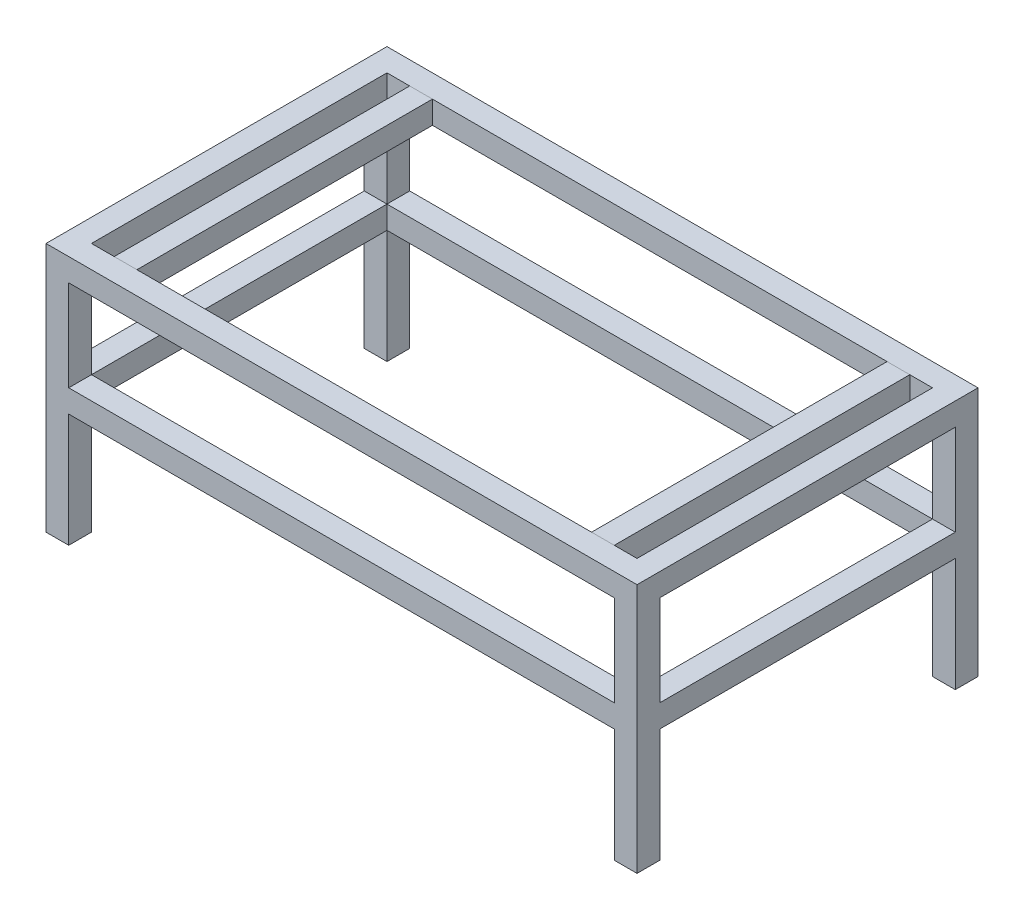
SolidWorks part; units mm, degrees
ref_plane "Plan de face" through (0, 0, 0) normal (0, 0, 1) x (1, 0, 0)
ref_plane "Plan de dessus" through (0, 0, 0) normal (0, 1, 0) x (1, 0, 0)
ref_plane "Plan de droite" through (0, 0, 0) normal (1, 0, 0) x (0, 0, -1)
sketch "Esquisse1" plane through (0, 0, 0) normal (0, 1, 0) x (1, 0, 0)
  line L1 (0, 0) -> (13000, 0)
  line L2 (0, 0) -> (0, 7500)
  line L3 (0, 7500) -> (13000, 7500)
  line L4 (13000, 0) -> (13000, 7500)
  line L5 (500, 7000) -> (12500, 7000)
  line L6 (500, 7000) -> (500, 500)
  line L7 (500, 500) -> (12500, 500)
  line L8 (12500, 7000) -> (12500, 500)
  dimension "D1" = 13000
  dimension "D2" = 7500
  dimension "D3" = 500
  dimension "D4" = 500
  dimension "D5" = 500
  dimension "D6" = 500
extrude "Boss.-Extru.1" add sketch "Esquisse1" against normal blind 5500
sketch "Esquisse2" plane through (0, 0, 0) normal (0, 0, 1) x (1, 0, 0)
  line L0 (0, 0) -> (13000, 0) construction
  line L1 (500, -500) -> (12500, -500)
  line L2 (500, -500) -> (500, -2500)
  line L3 (500, -2500) -> (12500, -2500)
  line L4 (12500, -500) -> (12500, -2500)
  line L5 (500, -3000) -> (12500, -3000)
  line L6 (500, -3000) -> (500, -5500)
  line L7 (500, -5500) -> (12500, -5500)
  line L8 (12500, -3000) -> (12500, -5500)
  line L9 (0, -5500) -> (13000, -5500) construction
  line L10 (13000, -5500) -> (13000, 0) construction
  line L11 (0, -5500) -> (0, 0) construction
  point P12 (12500, -4250)
  dimension "D1" = 500
  dimension "D2" = 500
  dimension "D3" = 2000
  dimension "D4" = 0
  dimension "D5" = 500
  dimension "D6" = 500
  dimension "D7" = 500
  dimension "D8" = 500
extrude "Enlèv. mat.-Extru.1" cut sketch "Esquisse2" against normal through all
sketch "Esquisse3" plane through (0, 0, 0) normal (-1, 0, 0) x (0, 0, 1)
  line L0 (-7500, -5500) -> (0, -5500) construction
  line L1 (-7000, -500) -> (-500, -500)
  line L2 (-7000, -500) -> (-7000, -2500)
  line L3 (-7000, -2500) -> (-500, -2500)
  line L4 (-500, -500) -> (-500, -2500)
  line L5 (-7000, -3000) -> (-500, -3000)
  line L6 (-7000, -3000) -> (-7000, -5500)
  line L7 (-7000, -5500) -> (-500, -5500)
  line L8 (-500, -3000) -> (-500, -5500)
  line L9 (-7500, 0) -> (0, 0) construction
  line L10 (0, -5500) -> (0, 0) construction
  line L11 (-7500, -5500) -> (-7500, 0) construction
  dimension "D1" = 500
  dimension "D2" = 500
  dimension "D3" = 500
  dimension "D4" = 500
  dimension "D5" = 500
  dimension "D6" = 2000
  dimension "D7" = 500
extrude "Enlèv. mat.-Extru.2" cut sketch "Esquisse3" against normal through all
sketch "Esquisse4" plane through (0, 0, 0) normal (0, 1, 0) x (1, 0, 0)
  line L0 (12500, 7000) -> (500, 7000) construction
  line L1 (1000, 7000) -> (1500, 7000)
  line L2 (1000, 7000) -> (1000, 500)
  line L3 (1000, 500) -> (1500, 500)
  line L4 (1500, 7000) -> (1500, 500)
  line L5 (500, 500) -> (12500, 500) construction
  line L6 (500, 7000) -> (500, 500) construction
  line L7 (11500, 7000) -> (12000, 7000)
  line L8 (11500, 7000) -> (11500, 500)
  line L9 (11500, 500) -> (12000, 500)
  line L10 (12000, 7000) -> (12000, 500)
  line L11 (12500, 500) -> (12500, 7000) construction
  dimension "D1" = 500
  dimension "D2" = 500
  dimension "D3" = 500
  dimension "D4" = 500
extrude "Boss.-Extru.2" add sketch "Esquisse4" against normal blind 500 separate body
